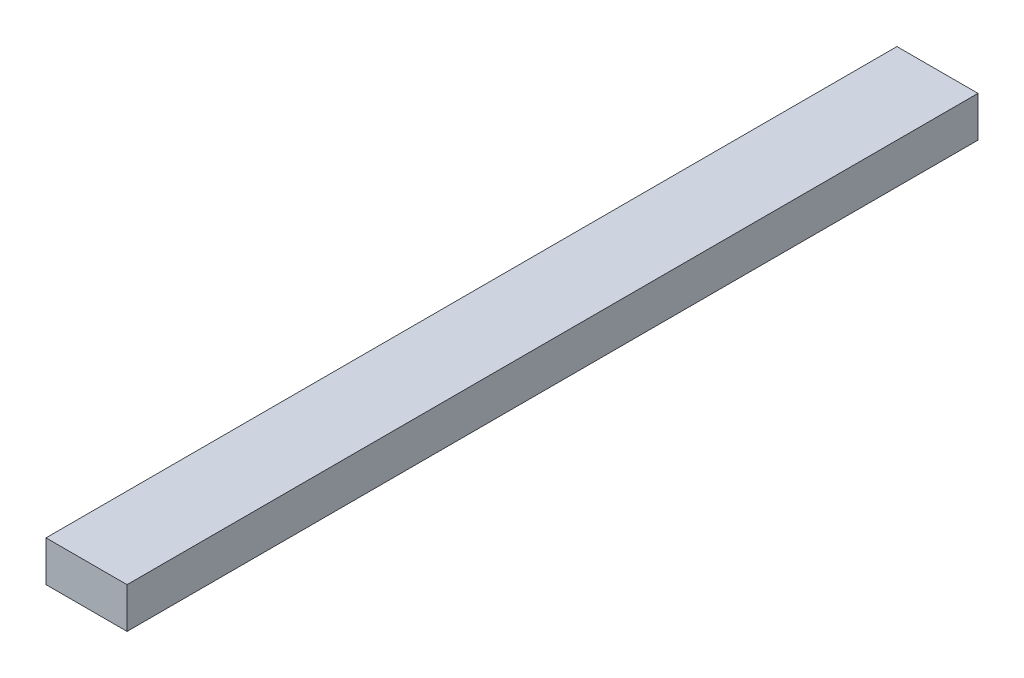
SolidWorks part; units mm, degrees
material "Custom Plastic"
ref_plane "Front Plane" through (0, 0, 0) normal (0, 0, 1) x (1, 0, 0)
ref_plane "Top Plane" through (0, 0, 0) normal (0, 1, 0) x (1, 0, 0)
ref_plane "Right Plane" through (0, 0, 0) normal (1, 0, 0) x (0, 0, -1)
sketch "Sketch1" plane through (0, 0, 0) normal (0, 0, 1) x (1, 0, 0)
  line L1 (-19.05, -9.525) -> (19.05, -9.525)
  line L2 (-19.05, -9.525) -> (-19.05, 9.525)
  line L3 (-19.05, 9.525) -> (19.05, 9.525)
  line L4 (19.05, -9.525) -> (19.05, 9.525)
  line L5 (-19.05, -9.525) -> (19.05, 9.525) construction
  line L6 (-19.05, 9.525) -> (19.05, -9.525) construction
  point P0 (0, 0)
extrude "Boss-Extrude1" add sketch "Sketch1" along normal blind 400
